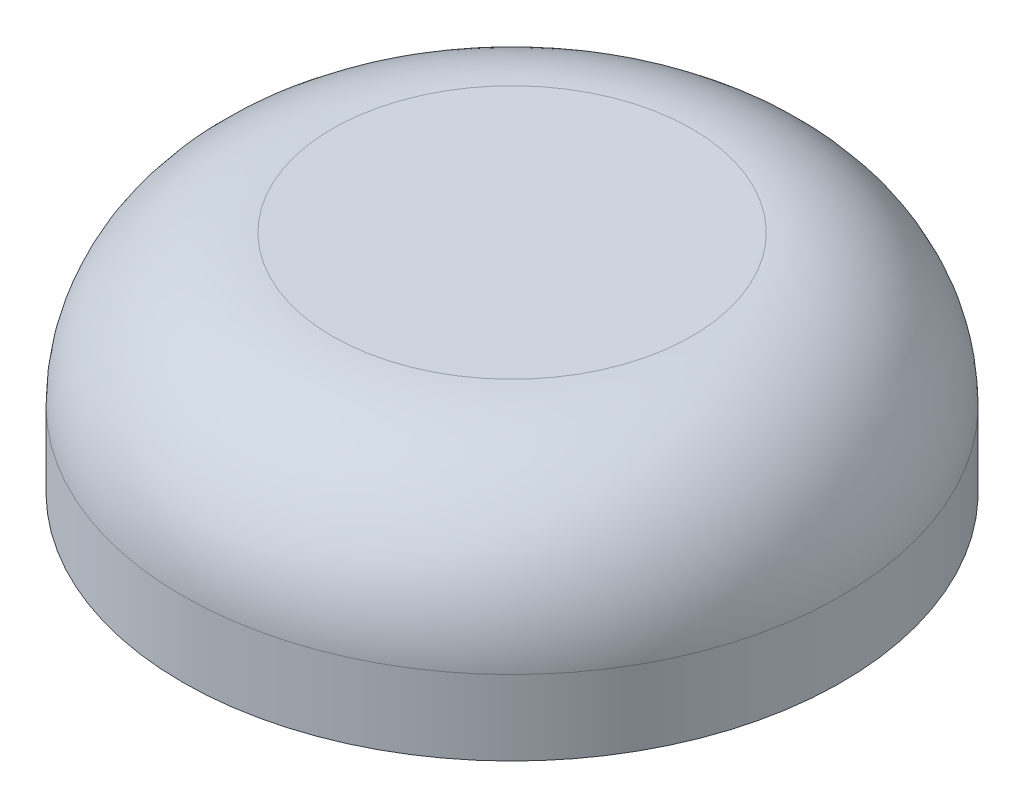
SolidWorks part; units mm, degrees
ref_plane "Front Plane" through (0, 0, 0) normal (0, 0, 1) x (1, 0, 0)
ref_plane "Top Plane" through (0, 0, 0) normal (0, 1, 0) x (1, 0, 0)
ref_plane "Right Plane" through (0, 0, 0) normal (1, 0, 0) x (0, 0, -1)
sketch "Sketch1" plane through (0, 0, 0) normal (0, 1, 0) x (1, 0, 0)
  circle A0 centre (0, 0) radius 4.4
  dimension "D1" = 8.8
extrude "Boss-Extrude1" add sketch "Sketch1" along normal blind 3
fillet "Fillet1" radius 2 1 edges at (0, 3, 4.4)
